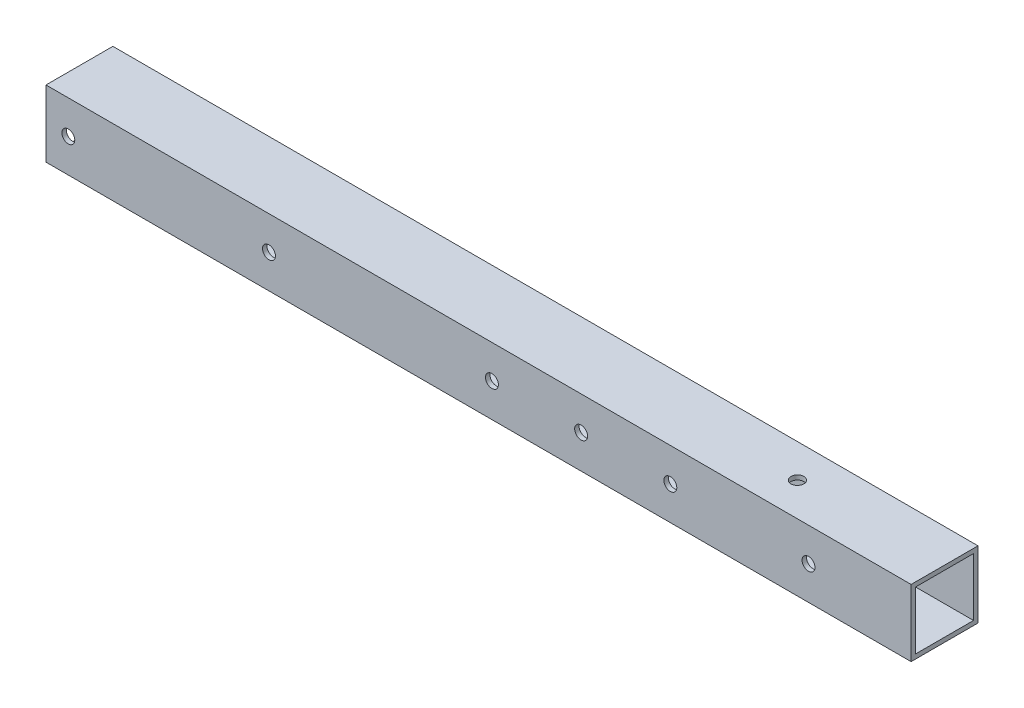
SolidWorks part; units mm, degrees
material "1060 合金"
ref_plane "前视基准面" through (0, 0, 0) normal (0, 0, 1) x (1, 0, 0)
ref_plane "上视基准面" through (0, 0, 0) normal (0, 1, 0) x (1, 0, 0)
ref_plane "右视基准面" through (0, 0, 0) normal (1, 0, 0) x (0, 0, -1)
other "Configuration Table"
sketch "草图1" plane through (0, 0, 0) normal (0, 1, 0) x (1, 0, 0)
  line L0 (0, 0) -> (194, 0)
  dimension "D1" = 194
other "铝管 15X15X1(1)"
ref_plane "基准面1" through (0, 0, 0) normal (1, 0, 0) x (0, 0, -1)
sketch "草图11" plane through (0, 0, 0) normal (1, 0, 0) x (0, 0, -1)
  line L1 (-7.5, -7.5) -> (7.5, -7.5)
  line L2 (-7.5, -7.5) -> (-7.5, 7.5)
  line L3 (-7.5, 7.5) -> (7.5, 7.5)
  line L4 (7.5, -7.5) -> (7.5, 7.5)
  line L5 (-7.5, -7.5) -> (7.5, 7.5) construction
  line L6 (-7.5, 7.5) -> (7.5, -7.5) construction
  line L7 (-6.5, -6.5) -> (6.5, -6.5)
  line L8 (-6.5, -6.5) -> (-6.5, 6.5)
  line L9 (-6.5, 6.5) -> (6.5, 6.5)
  line L10 (6.5, -6.5) -> (6.5, 6.5)
  line L11 (-6.5, -6.5) -> (6.5, 6.5) construction
  line L12 (-6.5, 6.5) -> (6.5, -6.5) construction
  point P0 (0, 0)
  point P6 (0, 0)
  point P11 (0, 0)
  dimension "D1" = 15
  dimension "D2" = 15
  dimension "D3" = 13
  dimension "D4" = 13
sketch "草图12" plane through (0, 0, -7.5) normal (0, 0, -1) x (-1, 0, 0)
  line L0 (0, 0) -> (-194, 0) construction
  circle A0 centre (-5, 0) radius 1.45
  circle A1 centre (-50, 0) radius 1.45
  dimension "D1" = 2.9
  dimension "D2" = 2.9
  dimension "D3" = 5
  dimension "D4" = 45
extrude "切除-拉伸1" cut sketch "草图12" against normal through all
sketch "草图13" plane through (0, 0, -7.5) normal (0, 0, -1) x (-1, 0, 0)
  line L0 (0, 0) -> (-194, 0) construction
  line L1 (-194, -7.5) -> (-194, 7.5) construction
  circle A0 centre (-171, 0) radius 1.45
  dimension "D1" = 2.9
  dimension "D2" = 23
extrude "切除-拉伸2" cut sketch "草图13" against normal through all
sketch "草图14" plane through (0, 7.5, 0) normal (0, 1, 0) x (1, 0, 0)
  line L0 (0, 0) -> (194, 0) construction
  line L1 (194, 7.5) -> (194, -7.5) construction
  circle A0 centre (161, 0) radius 1.45
  dimension "D1" = 2.9
  dimension "D2" = 33
extrude "切除-拉伸3" cut sketch "草图14" against normal through all
sketch "草图15" plane through (0, 0, -7.5) normal (0, 0, -1) x (-1, 0, 0)
  line L0 (-120, 7.5) -> (-120, -7.5) construction
  line L1 (-194, 7.5) -> (0, 7.5) construction
  line L2 (-194, -7.5) -> (0, -7.5) construction
  line L3 (0, -7.5) -> (0, 7.5) construction
  line L4 (0, 0) -> (-194, 0) construction
  circle A0 centre (-120, 0) radius 1.45
  circle A1 centre (-140, 0) radius 1.45
  circle A2 centre (-100, 0) radius 1.45
  dimension "D2" = 2.9
  dimension "D3" = 2.9
  dimension "D4" = 2.9
  dimension "D5" = 20
  dimension "D1" = 120
  dimension "D6" = 20
extrude "切除-拉伸4" cut sketch "草图15" against normal through all
